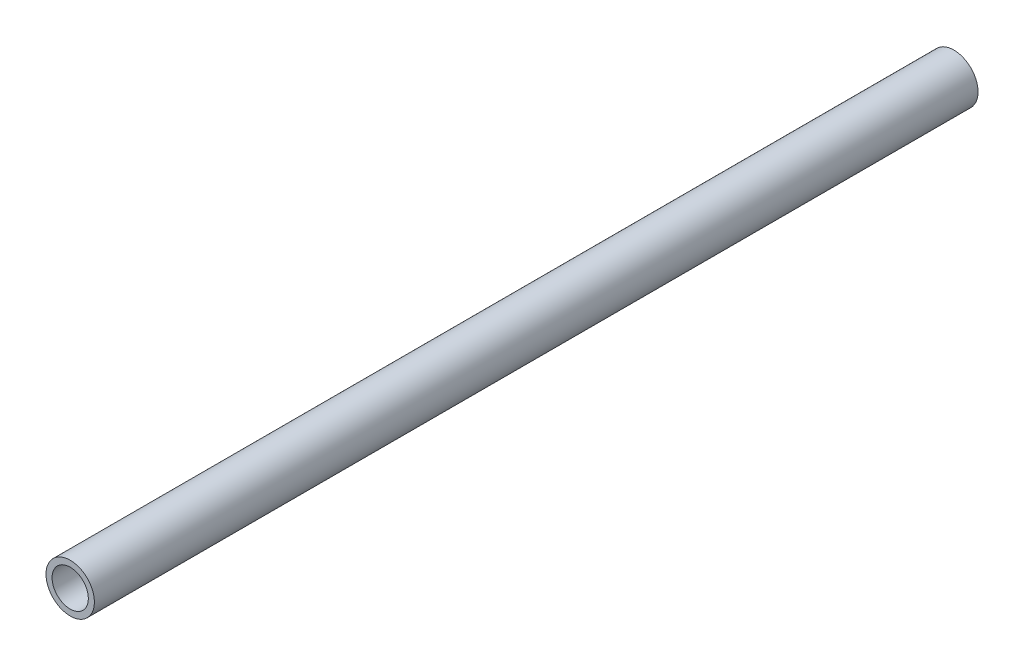
SolidWorks part; units mm, degrees
ref_plane "Front Plane" through (0, 0, 0) normal (0, 0, 1) x (1, 0, 0)
ref_plane "Top Plane" through (0, 0, 0) normal (0, 1, 0) x (1, 0, 0)
ref_plane "Right Plane" through (0, 0, 0) normal (1, 0, 0) x (0, 0, -1)
sketch "Sketch1" plane through (0, 0, 0) normal (0, 0, 1) x (1, 0, 0)
  circle A0 centre (0, 0) radius 6.35
  circle A1 centre (0, 0) radius 4.7625
extrude "Boss-Extrude1" add sketch "Sketch1" along normal blind 232
